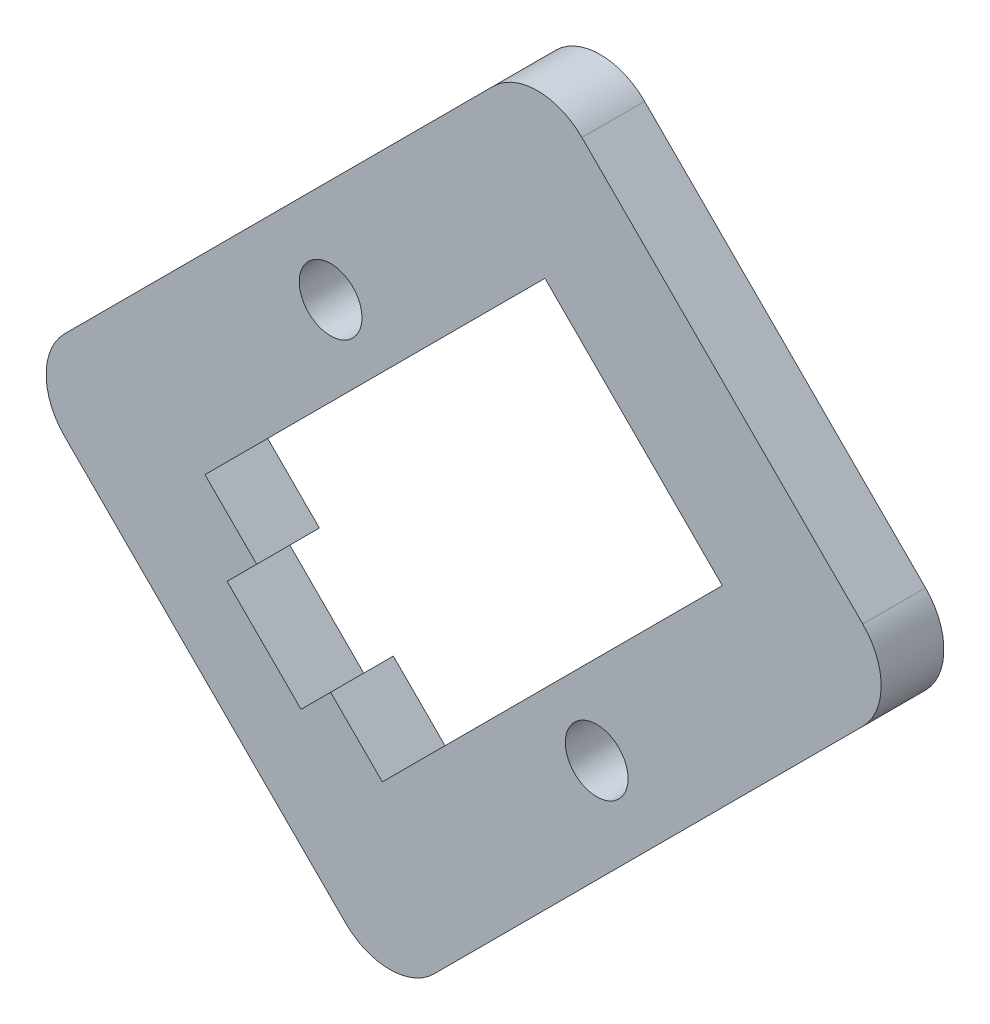
SolidWorks part; units mm, degrees
ref_plane "前基準面" through (0, 0, 0) normal (0, 0, 1) x (1, 0, 0)
ref_plane "上基準面" through (0, 0, 0) normal (0, 1, 0) x (1, 0, 0)
ref_plane "右基準面" through (0, 0, 0) normal (1, 0, 0) x (0, 0, -1)
sketch "草圖1" plane through (0, 0, 0) normal (0, 0, 1) x (1, 0, 0)
  line L0 (75.1442, 34.1005) -> (77.6191, 31.6256) construction
  line L1 (73.7299, 32.6862) -> (75.1442, 34.1005) construction
  line L2 (69.1338, 40.1109) -> (71.6087, 37.636) construction
  line L3 (71.6087, 37.636) -> (70.1944, 36.2217) construction
  line L4 (70.1944, 36.2217) -> (73.7299, 32.6862) construction
  line L5 (85.3973, 56.3743) -> (69.1338, 40.1109) construction
  line L6 (93.8825, 47.8891) -> (85.3973, 56.3743) construction
  line L7 (77.6191, 31.6256) -> (93.8825, 47.8891) construction
  line L8 (80.094, 24.9081) -> (100.6, 45.4142) construction
  line L9 (82.9224, 63.0918) -> (62.4163, 42.5857) construction
  line L10 (75.1442, 34.1005) -> (77.6191, 31.6256)
  line L11 (73.7299, 32.6862) -> (75.1442, 34.1005)
  line L12 (69.1338, 40.1109) -> (71.6087, 37.636)
  line L13 (71.6087, 37.636) -> (70.1944, 36.2217)
  line L14 (70.1944, 36.2217) -> (73.7299, 32.6862)
  line L15 (85.3973, 56.3743) -> (69.1338, 40.1109)
  line L16 (93.8825, 47.8891) -> (85.3973, 56.3743)
  line L17 (77.6191, 31.6256) -> (93.8825, 47.8891)
  line L18 (80.094, 24.9081) -> (100.6, 45.4142)
  line L19 (82.9224, 63.0918) -> (62.4163, 42.5857)
  line L20 (62.4163, 38.3431) -> (75.8513, 24.9081)
  line L21 (87.165, 63.0918) -> (100.6, 49.6568)
  circle A0 centre (75.1442, 50.3639) radius 1.5 construction
  circle A1 centre (87.8721, 37.636) radius 1.5 construction
  arc A2 (75.8513, 24.9081) -> (80.094, 24.9081) centre (77.9726, 27.0294) ccw construction
  arc A3 (62.4163, 42.5857) -> (62.4163, 38.3431) centre (64.5376, 40.4644) ccw construction
  arc A4 (100.6, 45.4142) -> (100.6, 49.6568) centre (98.4787, 47.5355) ccw construction
  arc A5 (87.165, 63.0918) -> (82.9224, 63.0918) centre (85.0437, 60.9705) ccw construction
  circle A6 centre (75.1442, 50.3639) radius 1.5
  circle A7 centre (87.8721, 37.636) radius 1.5
  arc A8 (75.8513, 24.9081) -> (80.094, 24.9081) centre (77.9726, 27.0294) ccw
  arc A9 (62.4163, 42.5857) -> (62.4163, 38.3431) centre (64.5376, 40.4644) ccw
  arc A10 (100.6, 45.4142) -> (100.6, 49.6568) centre (98.4787, 47.5355) ccw
  arc A11 (87.165, 63.0918) -> (82.9224, 63.0918) centre (85.0437, 60.9705) ccw
extrude "填料-伸長1" add sketch "草圖1" along normal blind 3
